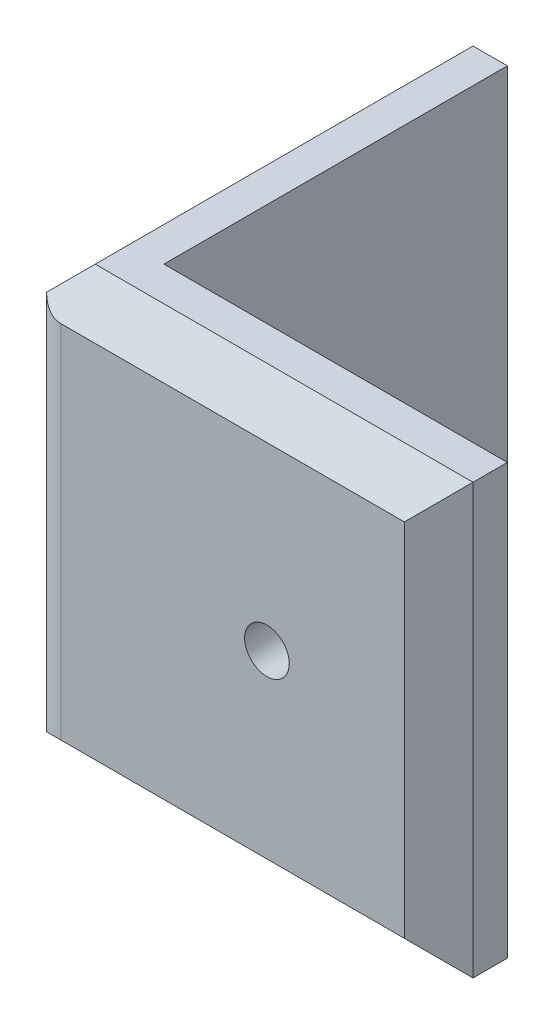
SolidWorks part; units mm, degrees
ref_plane "Front Plane" through (0, 0, 0) normal (0, 0, 1) x (1, 0, 0)
ref_plane "Top Plane" through (0, 0, 0) normal (0, 1, 0) x (1, 0, 0)
ref_plane "Right Plane" through (0, 0, 0) normal (1, 0, 0) x (0, 0, -1)
sketch "Sketch1" plane through (0, 0, 0) normal (0, 1, 0) x (1, 0, 0)
  line L0 (-8, 40) -> (0, 40)
  line L1 (0, 40) -> (0, 0)
  line L2 (0, 0) -> (40, 0)
  line L3 (40, 0) -> (40, -8)
  line L4 (40, -8) -> (-8, -8)
  line L5 (-8, -8) -> (-8, 40)
  dimension "D1" = 40
  dimension "D2" = 8
  dimension "D3" = 8
  dimension "D4" = 40
extrude "Boss-Extrude1" add sketch "Sketch1" along normal blind 50
sketch "Sketch2" plane through (-8, 0, 0) normal (-1, 0, 0) x (0, 0, 1)
  line L0 (8, 50) -> (8, 0) construction
  line L1 (8, 25) -> (-40, 25) construction
  line L2 (-40, 50) -> (-40, 0) construction
  circle A0 centre (-20, 25) radius 2.6
  point P8 (0, 0)
  dimension "D1" = 20
  dimension "D2" = 5.2
extrude "Cut-Extrude1" cut sketch "Sketch2" against normal through all
sketch "Sketch3" plane through (0, 0, 8) normal (0, 0, 1) x (1, 0, 0)
  line L0 (-8, 25) -> (40, 25) construction
  line L1 (-8, 50) -> (-8, 0) construction
  line L2 (40, 50) -> (40, 0) construction
  circle A0 centre (20, 25) radius 2.6
  point P8 (0, 0)
  dimension "D1" = 20
  dimension "D2" = 5.2
extrude "Cut-Extrude2" cut sketch "Sketch3" against normal through all
sketch "Sketch4" plane through (-8, 0, 0) normal (-1, 0, 0) x (0, 0, 1)
  circle A0 centre (-20, 25) radius 12.5
  circle A1 centre (-20, 25) radius 5.5
  dimension "D1" = 25
extrude "Boss-Extrude2" add sketch "Sketch4" along normal blind 8 draft 15 contours A0 | A1
fillet "Fillet1" radius 4 1 edges at (-8, 25, -7.5)
chamfer "Chamfer1" distance 4 angle 45 6 edges at (40, 25, 8) (16, 0, 8) (16, 50, 8) (-8, 0, -16) (-8, 50, -16) (-8, 25, -40)
fillet "Fillet2" radius 4 1 edges at (-8, 25, 8)
